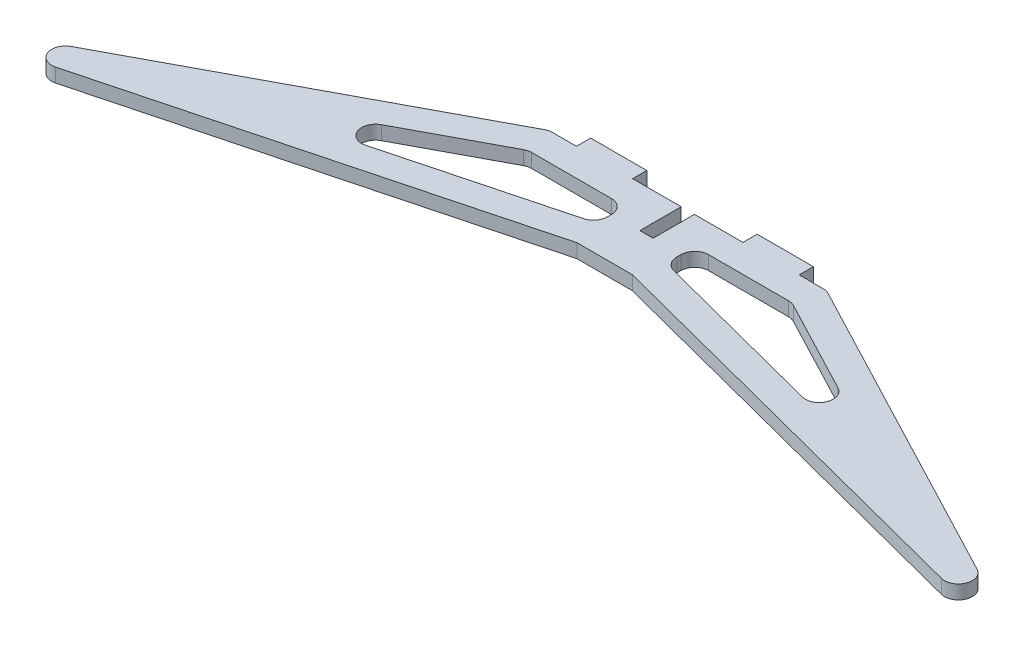
SolidWorks part; units mm, degrees
ref_plane "Front Plane" through (0, 0, 0) normal (0, 0, 1) x (1, 0, 0)
ref_plane "Top Plane" through (0, 0, 0) normal (0, 1, 0) x (1, 0, 0)
ref_plane "Right Plane" through (0, 0, 0) normal (1, 0, 0) x (0, 0, -1)
sketch "Sketch2" plane through (0, 0, 0) normal (0, 1, 0) x (1, 0, 0)
  line L0 (1.5113, 0) -> (12.6238, 0)
  line L4 (12.6238, 3.2512) -> (12.6238, 0)
  line L8 (12.6238, 3.2512) -> (25.4762, 3.2512)
  line L9 (-1.5113, 0) -> (-1.5113, -9.4488)
  line L10 (-1.5113, -9.4488) -> (1.5113, -9.4488)
  line L11 (25.4762, 3.2512) -> (25.4762, 0)
  line L12 (-12.6238, 0) -> (-1.5113, 0)
  line L13 (25.4762, 0) -> (30.968, 0)
  line L14 (1.5113, -9.4488) -> (1.5113, 0)
  line L15 (-52.0834, -18.0412) -> (-30.8629, -6.7235)
  line L16 (-25.4762, 3.2512) -> (-12.6238, 3.2512)
  line L17 (-25.4762, 0) -> (-30.9562, 0)
  line L18 (-103.0239, -38.0127) -> (-32.4504, -0.3735)
  line L19 (-100.7218, -43.8847) -> (-6.35, -19.05)
  line L20 (-6.35, -19.05) -> (6.35, -19.05)
  line L21 (-12.6238, 3.2512) -> (-12.6238, 0)
  line L22 (32.4425, -0.3632) -> (104.1649, -37.9739)
  line L23 (6.35, -19.05) -> (101.8924, -43.8589)
  line L24 (-25.4762, 3.2512) -> (-25.4762, 0)
  line L29 (-49.7813, -23.9131) -> (-10.3224, -13.5292)
  line L30 (-7.9554, -10.4725) -> (-7.9514, -9.5388)
  line L31 (7.9416, -9.5291) -> (7.9428, -10.4512)
  line L32 (10.3198, -13.5202) -> (50.0257, -23.8304)
  line L33 (30.8786, -6.7132) -> (52.2982, -17.9455)
  line L38 (-11.1263, -6.35) -> (-29.3688, -6.35)
  line L39 (11.1166, -6.35) -> (29.4041, -6.35)
  arc A0 (-100.7218, -43.8847) -> (-103.0239, -38.0127) centre (-101.5298, -40.8142) cw
  arc A1 (101.8924, -43.8589) -> (104.1649, -37.9739) centre (102.6904, -40.7858) ccw
  arc A2 (-30.9562, 0) -> (-32.4504, -0.3735) centre (-30.9562, -3.175) ccw
  arc A3 (30.968, 0) -> (32.4425, -0.3632) centre (30.968, -3.175) cw
  arc A4 (30.8786, -6.7132) -> (29.4041, -6.35) centre (29.4041, -9.525) ccw
  arc A5 (7.9416, -9.5291) -> (11.1166, -6.35) centre (11.1166, -9.525) cw
  arc A6 (-29.3688, -6.35) -> (-30.8629, -6.7235) centre (-29.3688, -9.525) ccw
  arc A7 (-7.9514, -9.5388) -> (-11.1263, -6.35) centre (-11.1263, -9.525) ccw
  arc A8 (-10.3224, -13.5292) -> (-7.9554, -10.4725) centre (-11.1304, -10.4587) ccw
  arc A9 (10.3198, -13.5202) -> (7.9428, -10.4512) centre (11.1178, -10.4471) cw
  arc A10 (50.0257, -23.8304) -> (52.2982, -17.9455) centre (50.8237, -20.7573) ccw
  arc A11 (-49.7813, -23.9131) -> (-52.0834, -18.0412) centre (-50.5893, -20.8426) cw
  dimension "D1" = 3.175
  dimension "D2" = 3.175
extrude "Boss-Extrude1" add sketch "Sketch2" along normal blind 3.175
